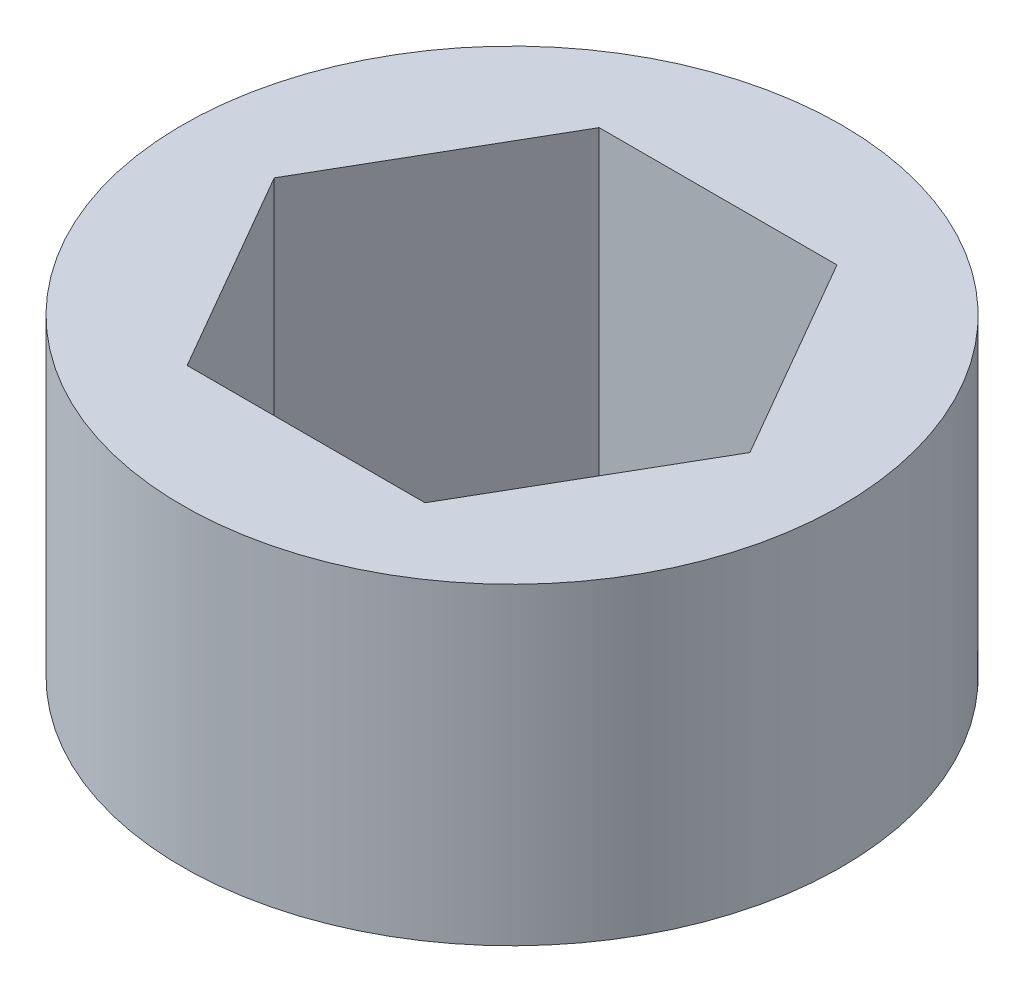
SolidWorks part; units mm, degrees
ref_plane "Front" through (0, 0, 0) normal (0, 0, 1) x (1, 0, 0)
ref_plane "Top" through (0, 0, 0) normal (0, 1, 0) x (1, 0, 0)
ref_plane "Right" through (0, 0, 0) normal (1, 0, 0) x (0, 0, -1)
sketch "Sketch1" plane through (0, 0, 0) normal (0, 1, 0) x (1, 0, 0)
  line L1 (2.8868, 0) -> (1.4434, 2.5)
  line L2 (1.4434, 2.5) -> (-1.4434, 2.5)
  line L3 (-1.4434, 2.5) -> (-2.8868, 0)
  line L4 (-2.8868, 0) -> (-1.4434, -2.5)
  line L5 (-1.4434, -2.5) -> (1.4434, -2.5)
  line L6 (1.4434, -2.5) -> (2.8868, 0)
  circle A0 centre (0, 0) radius 2.5 construction
  circle A1 centre (0, 0) radius 4
extrude "Boss-Extrude1" add sketch "Sketch1" along normal blind 3.8
